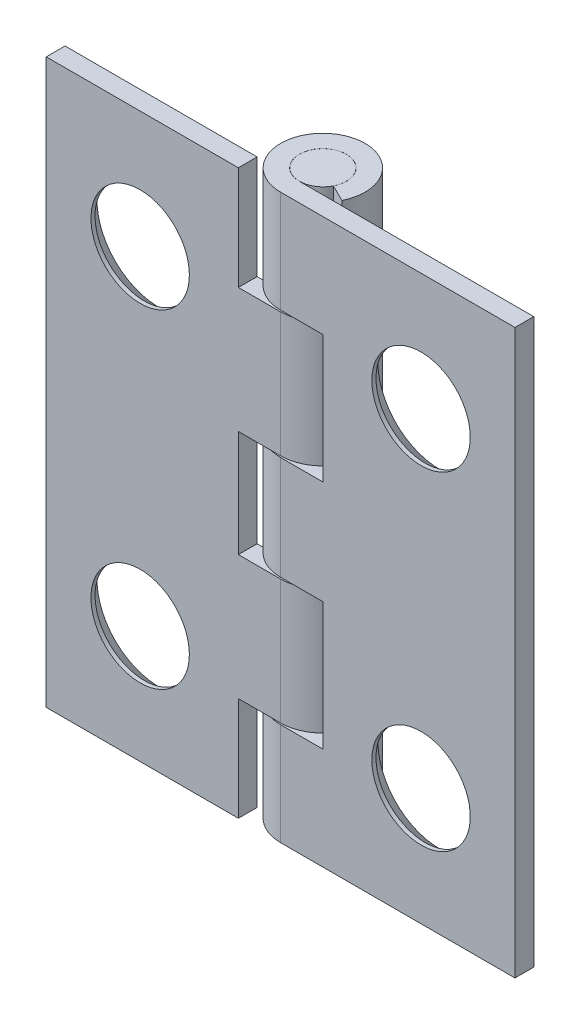
SolidWorks part; units mm, degrees
ref_plane "Front" through (0, 0, 0) normal (0, 0, 1) x (1, 0, 0)
ref_plane "Top" through (0, 0, 0) normal (0, 1, 0) x (1, 0, 0)
ref_plane "Right" through (0, 0, 0) normal (1, 0, 0) x (0, 0, -1)
sketch "Sketch1" plane through (0, 0, 0) normal (0, 1, 0) x (1, 0, 0)
  line L0 (0, -0.7937) -> (7.9248, -0.7937)
  line L1 (7.9248, -0.7937) -> (7.9248, -1.4287)
  line L2 (7.9248, -1.4287) -> (0, -1.4288)
  line L3 (1.2799, -0.635) -> (0.711, -0.3528)
  line L4 (0.711, -0.3528) -> (0, 0) construction
  line L5 (1.2799, -0.635) -> (1.2011, -0.7937) construction
  arc A0 (0.711, -0.3528) -> (0, -0.7937) centre (0, 0) ccw
  arc A1 (1.2799, -0.635) -> (0, -1.4288) centre (0, 0) ccw
  dimension "D1" = 0.1588
  dimension "K Pin Dia" = 1.5875
  dimension "B Half Width" = 7.9248
  dimension "M Mat'l Thickness" = 0.635
extrude "Extrude1" add sketch "Sketch1" along normal mid plane 19.05
ref_plane "Plane2" through (4.7498, 0, 0) normal (1, 0, 0) x (0, 0, -1)
sketch "Sketch7" plane through (4.7498, 0, 0) normal (1, 0, 0) x (0, 0, -1)
  line L0 (1.8223, 5.5562) -> (-3.6624, 5.5562) construction
  line L1 (-0.7937, 5.5562) -> (-0.7937, 7.6518)
  line L2 (-0.7937, 7.6518) -> (-1.2905, 7.2199)
  line L3 (-1.2905, 7.2199) -> (-1.4287, 7.2199)
  line L4 (-1.4287, 7.2199) -> (-1.4287, 5.5563)
  line L5 (-1.4287, 5.5563) -> (-0.7937, 5.5562)
  line L6 (-0.7937, 3.4607) -> (-1.2905, 3.8926) construction
  line L7 (-0.7937, 9.525) -> (-0.7937, -9.525) construction
  line L9 (-1.4287, 9.525) -> (-0.7937, 9.525) construction
  line L10 (-1.4287, 9.525) -> (-1.4287, -9.525) construction
  dimension "D1" = 82
  dimension "Screw Head Dia" = 4.191
  dimension "X Thru Dia" = 3.3274
  dimension "G" = 3.9688
revolve "Cut-Revolve1" cut sketch "Sketch7" angle 360 about L0
pattern_linear "LPattern2" count 2 spacing 11.1125 along (0, -1, 0) of "Cut-Revolve1"
mirror "Mirror2" about plane through (0, 0, 0) normal (1, 0, 0) of bodies 114 108
sketch "Sketch4" plane through (0, 0, 0) normal (0, 0, 1) x (1, 0, 0)
  line L0 (-1.4288, 9.525) -> (-1.4288, 6.0706) construction
  line L1 (-1.4288, 6.0706) -> (1.4288, 6.0706)
  line L2 (1.4288, 6.0706) -> (1.4288, 1.7526)
  line L3 (1.4288, 1.7526) -> (-1.4288, 1.7526)
  line L4 (-1.4288, 1.7526) -> (-1.4288, -1.7526) construction
  line L5 (-1.4288, -1.7526) -> (1.4288, -1.7526)
  line L6 (1.4288, -1.7526) -> (1.4288, -6.0706)
  line L7 (1.4288, -6.0706) -> (-1.4288, -6.0706)
  line L8 (-1.4288, -6.0706) -> (-1.4288, -9.525) construction
  line L9 (7.9248, -9.525) -> (0, -9.525) construction
  line L10 (7.9248, 9.525) -> (0, 9.525) construction
  line L11 (-1.4288, 9.525) -> (-1.4288, -9.525) construction
  line L12 (1.4288, -9.525) -> (1.4288, 9.525) construction
  line L13 (-1.4288, -6.0706) -> (-1.4288, -1.7526)
  line L14 (-1.4288, 1.7526) -> (-1.4288, 6.0706)
  dimension "D" = 3.5052
  dimension "C" = 12.1412
extrude "Cut-Extrude1" cut sketch "Sketch4" against normal through all and the other way through all
sketch "Sketch5" plane through (0, 0, 0) normal (0, 0, 1) x (1, 0, 0)
  line L0 (1.4288, -1.7526) -> (1.4288, -6.0706) construction
  line L1 (-1.4288, -9.525) -> (1.4288, -9.525)
  line L2 (-1.4288, -9.525) -> (-1.4288, -6.0198)
  line L3 (-1.4288, -6.0198) -> (1.4288, -6.0198)
  line L4 (1.4288, -9.525) -> (1.4288, -6.0198)
  line L5 (-1.4288, -6.0706) -> (-1.4288, -1.7526) construction
  line L6 (-1.4288, -1.8034) -> (1.4288, -1.8034)
  line L7 (-1.4288, -1.8034) -> (-1.4288, 1.8034)
  line L8 (-1.4288, 1.8034) -> (1.4288, 1.8034)
  line L9 (1.4288, -1.8034) -> (1.4288, 1.8034)
  line L10 (1.4288, 6.0706) -> (1.4288, 1.7526) construction
  line L11 (-1.4288, 6.0706) -> (1.4288, 6.0706) construction
  line L12 (-1.4288, 9.525) -> (1.4288, 9.525)
  line L13 (-1.4288, 9.525) -> (-1.4288, 6.0198)
  line L14 (-1.4288, 6.0198) -> (1.4288, 6.0198)
  line L15 (1.4288, 9.525) -> (1.4288, 6.0198)
  line L16 (1.4288, 1.7526) -> (-1.4288, 1.7526) construction
  line L17 (-1.4288, -1.7526) -> (1.4288, -1.7526) construction
  line L18 (1.4288, -6.0706) -> (-1.4288, -6.0706) construction
  dimension "D1" = 0.0508
  dimension "D2" = 0.0508
  dimension "D3" = 0.0508
  dimension "D4" = 0.0508
extrude "Cut-Extrude2" cut sketch "Sketch5" against normal through all and the other way through all
sketch "Sketch6" plane through (0, 0, 0) normal (0, 1, 0) x (1, 0, 0)
  line L0 (0, 0) -> (0, 0.7912) construction
  line L1 (0, 0.7912) -> (0, 0.7937) construction
  circle A0 centre (0, 0) radius 0.7912
  arc A1 (0.711, -0.3528) -> (0, -0.7937) centre (0, 0) ccw construction
  dimension "D1" = 0.0025
extrude "Extrude2" add sketch "Sketch6" against normal up to surface and the other way up to surface
equation "\"D1@Sketch1\"=\"M Mat'l Thickness@Sketch1\"/4"
